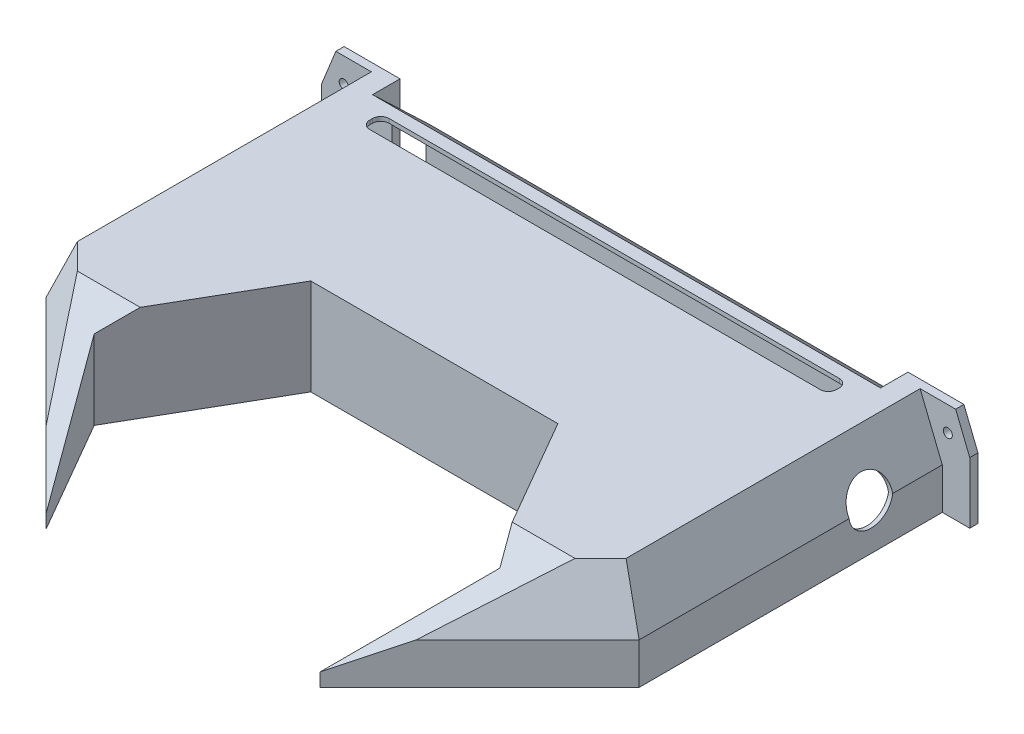
SolidWorks part; units mm, degrees
material "ABS"
ref_plane "Front" through (0, 0, 0) normal (0, 0, 1) x (1, 0, 0)
ref_plane "Top" through (0, 0, 0) normal (0, 1, 0) x (1, 0, 0)
ref_plane "Right" through (0, 0, 0) normal (1, 0, 0) x (0, 0, -1)
sketch "Esquisse1" plane through (0, 0, 0) normal (0, 1, 0) x (1, 0, 0)
  line L0 (-108, -33.4214) -> (-49.8885, -91.5328)
  line L2 (-108, -33.4214) -> (-108, 80)
  line L5 (-73.8675, -50) -> (-45, 0)
  line L6 (-45, 0) -> (0, 0)
  line L10 (-108, 80) -> (0, 80)
  line L11 (0, 80) -> (0, 0)
  line L12 (-73.8675, -50) -> (-49.8885, -91.5328)
  point P3 (-57.4572, -98.4235)
  point P9 (-74.1306, -50.4556)
  dimension "D1" = 60
  dimension "D2" = 45
  dimension "D3" = 45
  dimension "D4" = 80
  dimension "D5" = 100
  dimension "D6" = 108
  dimension "D7" = 120
  dimension "D8" = 50
extrude "Boss.-Extru.1" add sketch "Esquisse1" along normal blind 35
sketch "Esquisse2" plane through (0, 0, 0) normal (1, 0, 0) x (0, 0, -1)
  line L0 (-91.5328, 35) -> (-91.5328, 4.8885)
  line L2 (-91.5328, 4.8885) -> (-39.3782, 35)
  line L4 (-39.3782, 35) -> (-91.5328, 35)
  line L6 (-91.5328, 35) -> (-91.5328, 0) construction
  line L7 (0, 35) -> (80, 35) construction
  line L8 (0, 0) -> (80, 0) construction
  point P3 (-84.3334, 56.5662)
  point P4 (-100, 5.854)
  point P8 (33.7726, 40)
  dimension "D1" = 30
  dimension "D2" = 50
extrude "Enlèv. mat.-Extru.1" cut sketch "Esquisse2" against normal through all both and the other way through all
chamfer "Chanfrein2" distance 20 angle 22 2 edges at (-105.0216, 35, 36.3998) (-108, 35, -23.2893)
mirror "Symétrie1" about plane through (0, 35, -80) normal (-1, 0, 0) of bodies 102
sketch "Esquisse3" plane through (0, 0, 0) normal (1, 0, 0) x (0, 0, -1)
  line L0 (80, 25.4762) -> (91, 15)
  line L1 (91, 15) -> (91, 0)
  line L2 (91, 0) -> (80, 0)
  line L3 (80, 0) -> (80, 25.4762)
  line L4 (-33.4214, 15) -> (80, 15) construction
  line L5 (80, 35) -> (-30.0743, 35) construction
  point P3 (58.6476, 35)
  point P10 (70, 35)
  dimension "D1" = 11
  dimension "D2" = 46.397
  dimension "D3" = 10
extrude "Boss.-Extru.2" add sketch "Esquisse3" along normal mid plane 185
sketch "Esquisse4" plane through (92.5, 0, 0) normal (1, 0, 0) x (0, 0, -1)
  line L0 (91, 15) -> (70, 35)
  line L1 (91, 15) -> (80, 25.4762) construction
  line L2 (70, 35) -> (91, 35)
  line L3 (80, 35) -> (-30.0743, 35) construction
  line L4 (91, 35) -> (91, 15)
extrude "Enlèv. mat.-Extru.2" cut sketch "Esquisse4" against normal up to surface (185 mm away) up to face at (-92.5, 10.119, -85.5)
shell "Coque1" thickness 1.5
sketch "Esquisse5" plane through (-108, 0, 0) normal (-1, 0, 0) x (0, 0, 1)
  line L0 (-80, 0) -> (33.4214, 0) construction
  line L1 (-80, 15) -> (-80, 0) construction
  circle A0 centre (-51, 16) radius 8
  dimension "D1" = 16
  dimension "D2" = 29
  dimension "D3" = 16
extrude "Enlèv. mat.-Extru.3" cut sketch "Esquisse5" against normal through all
sketch "Esquisse6" plane through (0, 35, 0) normal (0, 1, 0) x (1, 0, 0)
  line L0 (-92.5, 80) -> (-99.9195, 80) construction
  line L1 (-85, 65.5) -> (85, 65.5)
  line L2 (-85, 65.5) -> (-85, 58.5)
  line L3 (-85, 58.5) -> (85, 58.5)
  line L4 (85, 65.5) -> (85, 58.5)
  line L5 (0, 58.5) -> (0, 65.5) construction
  line L6 (-85, 62) -> (85, 62) construction
  point P0 (0, 62)
  point P4 (0, 0)
  dimension "D1" = 18
  dimension "D2" = 7
  dimension "D3" = 170
extrude "Enlèv. mat.-Extru.4" cut sketch "Esquisse6" against normal through all
fillet "Congé1" radius 3 4 edges at (-85, 34.25, -58.5) (-85, 34.25, -65.5) (85, 34.25, -58.5) (85, 34.25, -65.5)
sketch "Esquisse7" plane through (0, 0, -80) normal (0, 0, -1) x (-1, 0, 0)
  line L0 (-99.9195, 35) -> (-92.5, 35) construction
  line L1 (-92.5, 0) -> (-118, 0)
  line L2 (-92.5, 0) -> (-92.5, 35)
  line L3 (-92.5, 35) -> (-112.8619, 35)
  line L5 (92.5, 35) -> (99.9195, 35) construction
  line L6 (92.5, 0) -> (118, 0)
  line L7 (92.5, 0) -> (92.5, 35)
  line L8 (92.5, 35) -> (112.8619, 35)
  line L10 (0, 50) -> (0, -50) construction
  line L11 (-112.8619, 35) -> (-118, 22.2827)
  line L12 (-118, 22.2827) -> (-118, 0)
  line L13 (118, 22.2827) -> (118, 0)
  line L14 (112.8619, 35) -> (118, 22.2827)
  line L15 (-108, 15) -> (-99.9195, 35) construction
  line L16 (-108, 15) -> (-108, 0) construction
  circle A0 centre (-110, 26.0666) radius 1.65
  circle A1 centre (110, 26.0666) radius 1.65
  circle A2 centre (-110, 26.0666) radius 3 construction
  point P23 (-118, -0.4881)
  point P24 (-112.7854, 35)
  point P27 (0, 0)
  dimension "D2" = 3.3
  dimension "D3" = 220
  dimension "D4" = 8.9334
  dimension "D5" = 6
  dimension "D7" = 10
  dimension "D8" = 6
  dimension "D1" = 236
  dimension "D6" = 12
extrude "Boss.-Extru.3" add sketch "Esquisse7" against normal blind 3
sketch "Esquisse8" plane through (92.5, 0, 0) normal (-1, 0, 0) x (0, 0, 1)
  line L4 (-78.5, 0) -> (-78.5, 24.8333)
  line L5 (-78.5, 24.8333) -> (-89.5, 14.3571)
  line L6 (-89.5, 14.3571) -> (-89.5, 0)
  line L7 (-89.5, 0) -> (-78.5, 0)
  line L8 (-78.5, 0) -> (-78.5, 24.8333)
  line L9 (-78.5, 24.8333) -> (-89.5, 14.3571)
  line L10 (-89.5, 14.3571) -> (-89.5, 0)
  line L11 (-89.5, 0) -> (-78.5, 0)
  dimension "D1" = 0
extrude "Enlèv. mat.-Extru.5" cut sketch "Esquisse8" along normal up to surface (185 mm away) up to face at (-92.5, 12.7738, -77.75)
